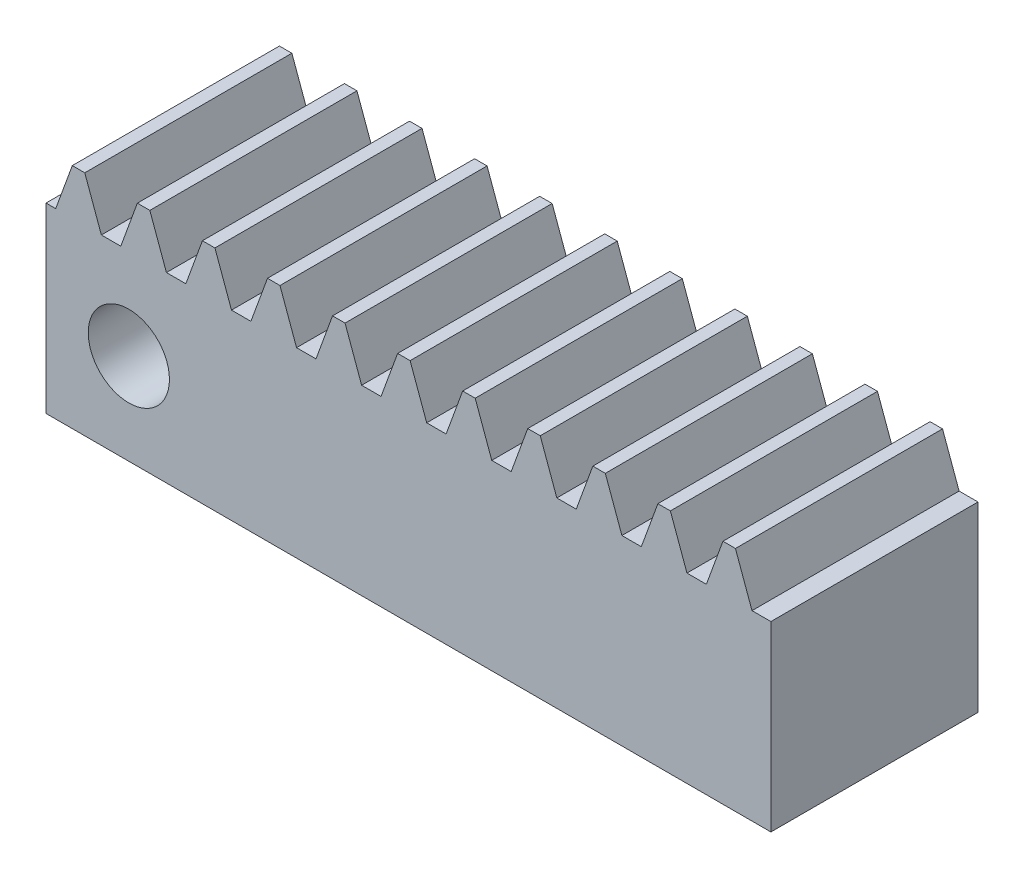
SolidWorks part; units mm, degrees
material "Cast Alloy Steel"
ref_plane "Plane1" through (0, 0, 0) normal (0, 0, 1) x (1, 0, 0)
ref_plane "Plane2" through (0, 0, 0) normal (0, 1, 0) x (1, 0, 0)
ref_plane "Plane3" through (0, 0, 0) normal (1, 0, 0) x (0, 0, -1)
sketch "HoldingSke" plane through (0, 0, 0) normal (0, 1, 0) x (1, 0, 0)
  line L0 (0, 0) -> (389.1506, -326.5361)
  line L1 (-15, 0) -> (100, 0) construction
  line L2 (0, 0) -> (-2.1039, 2.3779)
  line L3 (0, 0) -> (-11.863, 4.5341)
  line L4 (0, 0) -> (8.4147, 1.9427)
  line L5 (0, 0) -> (-23.7986, -8.8762)
  line L6 (0, 0) -> (-10.5278, -7.1032)
  line L9 (-71.009, 38.7566) -> (-29.2396, 53.9594)
  line L10 (-76.2, 71.12) -> (-63.5, 71.12)
  line L11 (0, 0) -> (-12.7, 0)
  line L12 (-76.2, 101.6) -> (-76.1492, 101.6)
  line L13 (24.9733, 27.94) -> (52.9518, 28.4284)
  line L14 (24.9733, 27.94) -> (25.0241, 27.9398)
  line L15 (24.9733, 27.94) -> (100.4021, 29.52)
  circle A0 centre (0, 0) radius 19.05
  circle A1 centre (0, 0) radius 6.35
  circle A2 centre (0, 0) radius 12.7
  dimension "MPH" = 12.7
  dimension "Diameter" = 38.1
  dimension "Num_teeth" = 13
  dimension "Pitch" = 508
  dimension "Width" = 12.7
  dimension "Show_teeth" = 400
  dimension "Thickness" = 12.7
  dimension "Ap" = 20
  dimension "Pitch_height" = 12.7
  dimension "Backlash" = 0.0508
  dimension "Addendum_fac" = 1
  dimension "Dedendum_fac" = 1.2
  dimension "Clearance_fac" = 0.2
  dimension "Dedendum_add" = 0.0508
  dimension "Length" = 44.45
sketch "BlankSke" plane through (0, 0, 0) normal (0, 0, 1) x (1, 0, 0)
  line L1 (0, 0) -> (44.45, 0)
  line L2 (0, 0) -> (0, 13.97)
  line L3 (0, 13.97) -> (44.45, 13.97)
  line L4 (44.45, 0) -> (44.45, 13.97)
  dimension "Length" = 44.45
  dimension "Blank_height" = 13.97
extrude "Blank" add sketch "BlankSke" against normal blind 12.7
sketch "TooCutSkeIll" plane through (0, 0, 0) normal (0, 0, 1) x (1, 0, 0)
  line L0 (-1.5999, 13.9366) -> (-0.6682, 11.3766)
  line L1 (-0.3817, 11.176) -> (0.3817, 11.176)
  line L2 (0.6682, 11.3766) -> (1.5999, 13.9366)
  line L3 (44.45, 13.97) -> (0, 13.97) construction
  line L4 (0, 0) -> (0, 64.897) construction
  line L5 (-13.208, 12.7) -> (12.954, 12.7) construction
  line L6 (0, 0) -> (44.45, 0) construction
  line L7 (1.1499, 12.7) -> (1.1499, 48.7463) construction
  line L8 (-1.1499, 12.7) -> (-1.1499, 48.7463) construction
  line L9 (1.6477, 13.97) -> (1.6477, 13.9954)
  line L10 (-1.6477, 13.97) -> (-1.6477, 13.9954)
  line L11 (-1.6477, 13.9954) -> (1.6477, 13.9954)
  arc A0 (0.3817, 11.176) -> (0.6682, 11.3766) centre (0.3817, 11.4808) ccw
  arc A1 (-0.6682, 11.3766) -> (-0.3817, 11.176) centre (-0.3817, 11.4808) ccw
  arc A2 (1.6477, 13.97) -> (1.5999, 13.9366) centre (1.6477, 13.9192) ccw
  arc A3 (-1.5999, 13.9366) -> (-1.6477, 13.97) centre (-1.6477, 13.9192) ccw
  dimension "Root_fillet" = 0.3048
  dimension "Break_rad" = 0.0508
  dimension "Pitch_height" = 12.7
  dimension "Gap_width" = 2.2997
  dimension "Dedendum" = 1.524
  dimension "Addendum_plus" = 1.2954
  dimension "Pressure_angle" = 20
extrude "ToothCutIll" [suppressed] cut sketch "TooCutSkeIll" against normal through all
sketch "TooCutSkeSim" plane through (0, 0, 0) normal (0, 0, 1) x (1, 0, 0)
  line L0 (0.5952, 11.176) -> (-0.5952, 11.176)
  line L1 (1.6213, 13.9954) -> (0.5952, 11.176)
  line L2 (0, 17.4625) -> (0, 53.467) construction
  line L3 (1.6213, 13.9954) -> (-1.6213, 13.9954)
  line L6 (-1.6213, 13.9954) -> (-0.5952, 11.176)
  line L9 (-1.1499, 12.7) -> (1.1499, 12.7) construction
  line L10 (0, 0) -> (44.45, 0) construction
  line L11 (1.1499, 12.7) -> (1.1499, 53.467) construction
  line L12 (-1.1499, 12.7) -> (-1.1499, 53.467) construction
  dimension "Pitch_height" = 12.7
  dimension "Pressure_angle" = 20
  dimension "Gap_width" = 2.2997
  dimension "Dedendum" = 1.524
  dimension "Addendum_plus" = 1.2954
extrude "ToothCutSim" cut sketch "TooCutSkeSim" against normal through all
pattern_linear "TeethCuts" count 12 spacing 3.9898 along (1, 0, 0) of "ToothCutIll", "ToothCutSim"
sketch "Sketch1" plane through (0, 0, 0) normal (0, 0, 1) x (1, 0, 0)
  line L0 (0, 11.176) -> (0, 0) construction
  line L1 (0, 0) -> (44.45, 0) construction
  circle A0 centre (5.08, 5.588) radius 2.4892
  dimension "D1" = 4.9784
  dimension "D2" = 5.08
  dimension "D3" = 5.588
extrude "Cut-Extrude1" cut sketch "Sketch1" against normal up to next
equation "' \"Pitch@HoldingSke\" = 4"
equation "' \"Num_teeth@HoldingSke\" = 12"
equation "' \"Ap@HoldingSke\" =  20"
equation "' \"Width@HoldingSke\" = 0.25"
equation "' \"Show_teeth@HoldingSke\" = 500"
equation "' \"Backlash@HoldingSke\" = 0.009"
equation "' \"Addendum_fac@HoldingSke\" = 1.0"
equation "' \"Dedendum_fac@HoldingSke\" = 1.25"
equation "' \"Dedendum_add@HoldingSke\" = 0.00005"
equation "' \"Clearance_fac@HoldingSke\" = 0.25"
equation "' \"Pitch_height@HoldingSke\" = 1"
equation "' \"Length@HoldingSke\" = 4.71"
equation "\"MPH@HoldingSke\" = \"Dedendum_fac@HoldingSke\" / \"Pitch@HoldingSke\" + 2 * \"Dedendum_add@HoldingSke\" + 0.002"
equation "\"MPH@HoldingSke\" = ((sgn( \"MPH@HoldingSke\" - \"Pitch_height@HoldingSke\")+1)*( \"MPH@HoldingSke\" - \"Pitch_height@HoldingSke\"))/2 + \"Pitch_height@HoldingSke\""
equation "\"Blank_height@BlankSke\" = \"Pitch_height@HoldingSke\" + \"Addendum_fac@HoldingSke\"  / \"Pitch@HoldingSke\" "
equation "\"Length@BlankSke\" =  \"Length@HoldingSke\""
equation "\"Face_width@Blank\" = \"Width@HoldingSke\""
equation "\"Pressure_angle@TooCutSkeIll\" = \"Ap@HoldingSke\""
equation "\"Addendum_plus@TooCutSkeIll\" =  \"Addendum_fac@HoldingSke\"  / \"Pitch@HoldingSke\" + 0.001"
equation "\"Dedendum@TooCutSkeIll\" = \"Dedendum_fac@HoldingSke\"  / \"Pitch@HoldingSke\""
equation "\"Pitch_height@TooCutSkeIll\" =  \"MPH@HoldingSke\""
equation "\"Gap_width@TooCutSkeIll\" = 3.14159265 / 2 / \"Pitch@HoldingSke\" + 6 * \"Backlash@HoldingSke\""
equation "\"Pressure_angle@TooCutSkeSim\" = \"Ap@HoldingSke\""
equation "\"Addendum_plus@TooCutSkeSim\" =  \"Addendum_fac@HoldingSke\"  / \"Pitch@HoldingSke\" + 0.001"
equation "\"Dedendum@TooCutSkeSim\" = \"Dedendum_fac@HoldingSke\"  / \"Pitch@HoldingSke\""
equation "\"Pitch_height@TooCutSkeSim\" =  \"MPH@HoldingSke\""
equation "\"Gap_width@TooCutSkeSim\" = 3.14159265 / 2 / \"Pitch@HoldingSke\" + 6 * \"Backlash@HoldingSke\""
equation "\"Root_fillet@TooCutSkeIll\" = \"Clearance_fac@HoldingSke\" / \"Pitch@HoldingSke\" + \"Dedendum_add@HoldingSke\""
equation "\"Break_rad@TooCutSkeIll\" = 0.02 / \"Pitch@HoldingSke\" * 2"
equation "\"Linear_pitch@TeethCuts\" = 3.14159265 / \"Pitch@HoldingSke\""
equation "\"Num_teeth@HoldingSke\" = int( ( \"Length@HoldingSke\" + 0 ) / (3.14159265 / \"Pitch@HoldingSke\")) + 0.9999  + 1"
equation " \"Num_teeth@TeethCuts\" = int( \"Show_teeth@HoldingSke\" ) + 1"
equation " \"Num_teeth@TeethCuts\" = ((sgn( \"Num_teeth@TeethCuts\" - \"Num_teeth@HoldingSke\" )-1)*( \"Num_teeth@TeethCuts\" - \"Num_teeth@HoldingSke\" ))/-2+ \"Num_teeth@HoldingSke\""
equation " \"Num_teeth@TeethCuts\" = ((sgn( \"Num_teeth@TeethCuts\" - 2.0)+1)*( \"Num_teeth@TeethCuts\" - 2.0))/2 +2.0"
